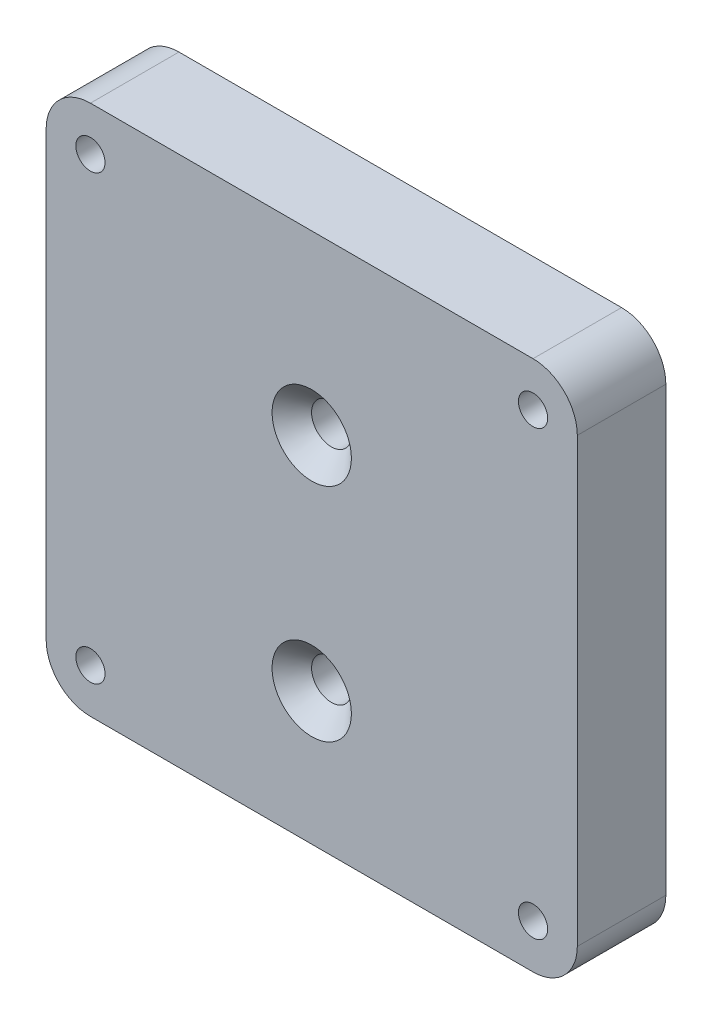
SolidWorks part; units mm, degrees
material "6061-T6 (SS)"
ref_plane "Front Plane" through (0, 0, 0) normal (0, 0, 1) x (1, 0, 0)
ref_plane "Top Plane" through (0, 0, 0) normal (0, 1, 0) x (1, 0, 0)
ref_plane "Right Plane" through (0, 0, 0) normal (1, 0, 0) x (0, 0, -1)
sketch "Sketch1" plane through (0, 0, 0) normal (0, 0, 1) x (1, 0, 0)
  line L0 (0, 0) -> (60, 0)
  line L1 (60, 0) -> (60, 60)
  line L2 (60, 60) -> (0, 60)
  line L3 (0, 60) -> (0, 0)
  dimension "D1" = 60
  dimension "D2" = 60
extrude "Boss-Extrude1" add sketch "Sketch1" along normal blind 10
sketch "Sketch2" plane through (0, 0, 10) normal (0, 0, 1) x (1, 0, 0)
  line L0 (5, 55) -> (55, 55) construction
  line L1 (55, 55) -> (55, 5) construction
  line L2 (55, 5) -> (5, 5) construction
  line L3 (5, 5) -> (5, 55) construction
  line L6 (7.1326, 0) -> (7.1326, 5) construction
  line L7 (0, 0) -> (60, 0) construction
  line L8 (7.1326, 5) -> (72.703, 5) construction
  line L9 (72.703, 5) -> (72.703, 0) construction
  line L10 (0, 0) -> (60, 60) construction
  line L11 (60, 60) -> (0, 60) construction
  line L12 (0, 60) -> (60, 0) construction
  line L13 (30, 30) -> (-38.5064, 30) construction
  line L14 (30, 30) -> (30, -18.0843) construction
  line L15 (0, 60) -> (0, 0) construction
  dimension "D1" = 25
  dimension "D2" = 50
  dimension "D3" = 50
  dimension "D4" = 25
  dimension "D5" = 5
hole_wizard "M4 Tapped Hole1" positions "Sketch3" profile "Sketch4" tap size "M4" standard "ISO"
sketch "Sketch3" plane through (0, 0, 10) normal (0, 0, 1) x (1, 0, 0)
  point P0 (5, 55)
  point P3 (55, 55)
  point P6 (55, 5)
  point P9 (5, 5)
sketch "Sketch4" plane through (5, 55, 10) normal (1, 0, 0) x (0, -1, 0)
  line L0 (0, 0) -> (0, 8.1)
  line L1 (0, 8.1) -> (1.65, 7.1086)
  line L2 (1.65, 7.1086) -> (1.65, 0)
  line L5 (1.65, 0) -> (0, 0)
  line L10 (0, 8.1) -> (-1.65, 7.1086) construction
  line L11 (0, -6.35) -> (0, 107.95) construction
  dimension "Tap Drill Dia." = 3.3
  dimension "Tap Drill Depth" = 8.1
  dimension "Drill Angle" = 118
cosmetic thread "Hole Thread1" parameters "D1"=6, "D2"=4
cosmetic thread "Hole Thread4" parameters "D1"=6, "D2"=4
cosmetic thread "Hole Thread8" parameters "D1"=6, "D2"=4
cosmetic thread "Hole Thread9" parameters "D1"=6, "D2"=4
sketch "Sketch5" plane through (0, 0, 0) normal (0, 0, -1) x (-1, 0, 0)
  line L0 (-30, 60) -> (-30, 0) construction
  line L1 (-60, 60) -> (0, 60) construction
  line L2 (0, 0) -> (-60, 0) construction
  line L3 (-46.5602, 40) -> (-32.2098, 40) construction
  line L4 (-47.2162, 15) -> (-33.7678, 15) construction
  dimension "D1" = 25
  dimension "D2" = 15
hole_wizard "CSK for M4 Hex Socket Countersunk Cap Screw1" positions "Sketch6" profile "Sketch7" countersink size "M4" standard "ISO" end condition through all
sketch "Sketch6" plane through (0, 0, 10) normal (0, 0, 1) x (1, 0, 0)
  line L0 (30, 60) -> (30, 0) construction
  line L1 (46.5602, 40) -> (32.2098, 40) construction
  line L2 (47.2162, 15) -> (33.7678, 15) construction
  point P0 (30, 40)
  point P6 (30, 15)
sketch "Sketch7" plane through (30, 40, 10) normal (1, 0, 0) x (0, -1, 0)
  line L0 (0, 0) -> (0, 10)
  line L1 (0, 10) -> (2.25, 10)
  line L2 (2.25, 10) -> (2.25, 2.23)
  line L3 (2.25, 2.23) -> (4.48, 0)
  line L5 (4.48, 0) -> (0, 0)
  line L6 (-2.25, 2.23) -> (-4.48, 0) construction
  line L11 (0, -6.35) -> (0, 107.95) construction
  dimension "Thru Hole Dia." = 4.5
  dimension "Thru Hole Depth" = 10
  dimension "Near C'Sink Dia." = 8.96
  dimension "Near C'Sink Angle" = 90
sketch "Sketch8" plane through (0, 0, 0) normal (0, -1, 0) x (1, 0, 0)
  line L0 (0, 5) -> (60, 5) construction
  line L1 (0, 10) -> (0, 0) construction
  line L2 (60, 10) -> (60, 0) construction
  circle A0 centre (14, 5) radius 2.3908
  circle A1 centre (30, 5) radius 3.6397
  circle A2 centre (46, 5) radius 2.8607
  dimension "D1" = 14
  dimension "D2" = 14
  dimension "D3" = 30
hole_wizard "M4 Tapped Hole2" positions "Sketch9" profile "Sketch10" tap size "M4" standard "ISO"
sketch "Sketch9" plane through (0, 0, 0) normal (0, -1, 0) x (-1, 0, 0)
  point P0 (-30, -5)
  point P3 (-14, -5)
  point P6 (-46, -5)
cosmetic thread "Hole Thread5" parameters "D1"=60, "D2"=4
cosmetic thread "Hole Thread6" parameters "D1"=60, "D2"=4
cosmetic thread "Hole Thread7" parameters "D1"=60, "D2"=4
sketch "Sketch10" plane through (30, 0, 5) normal (1, 0, 0) x (0, 0, -1)
  line L0 (0, 0) -> (0, 8.9914)
  line L1 (0, 8.9914) -> (1.65, 8)
  line L2 (1.65, 8) -> (1.65, 0)
  line L5 (1.65, 0) -> (0, 0)
  line L10 (0, 8.9914) -> (-1.65, 8) construction
  line L11 (0, -6.35) -> (0, 107.95) construction
  dimension "Tap Drill Dia." = 3.3
  dimension "Tap Drill Depth" = 8
  dimension "Drill Angle" = 118
fillet "Fillet1" radius 5 4 edges at (0, 60, 5) (60, 60, 5) (60, 0, 5) (0, 0, 5)
